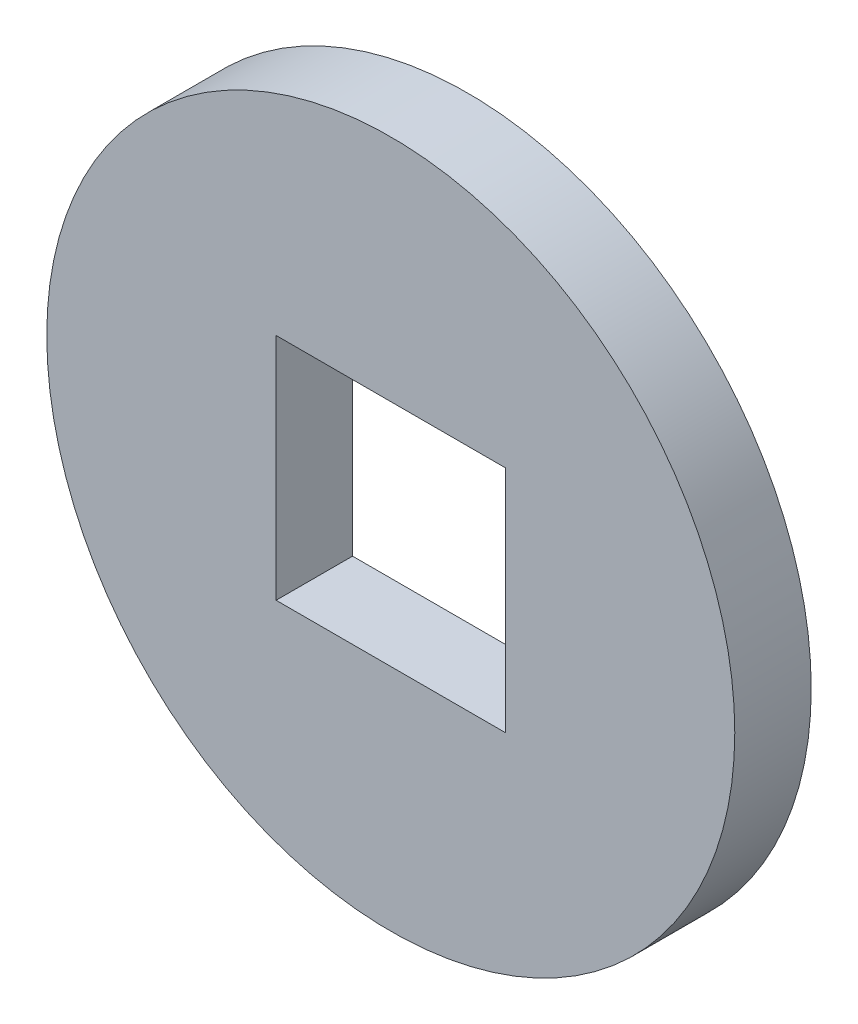
SolidWorks part; units mm, degrees
ref_plane "前视基准面" through (0, 0, 0) normal (0, 0, 1) x (1, 0, 0)
ref_plane "上视基准面" through (0, 0, 0) normal (0, 1, 0) x (1, 0, 0)
ref_plane "右视基准面" through (0, 0, 0) normal (1, 0, 0) x (0, 0, -1)
sketch "草图1" plane through (0, 0, 0) normal (0, 0, 1) x (1, 0, 0)
  line L1 (1.5, 1.5) -> (-1.5, 1.5)
  line L2 (1.5, 1.5) -> (1.5, -1.5)
  line L3 (1.5, -1.5) -> (-1.5, -1.5)
  line L4 (-1.5, 1.5) -> (-1.5, -1.5)
  line L5 (1.5, 1.5) -> (-1.5, -1.5) construction
  line L6 (1.5, -1.5) -> (-1.5, 1.5) construction
  circle A0 centre (0, 0) radius 4.5
  dimension "D1" = 9
  dimension "D2" = 3
  dimension "D3" = 3
extrude "凸台-拉伸1" add sketch "草图1" along normal blind 1
